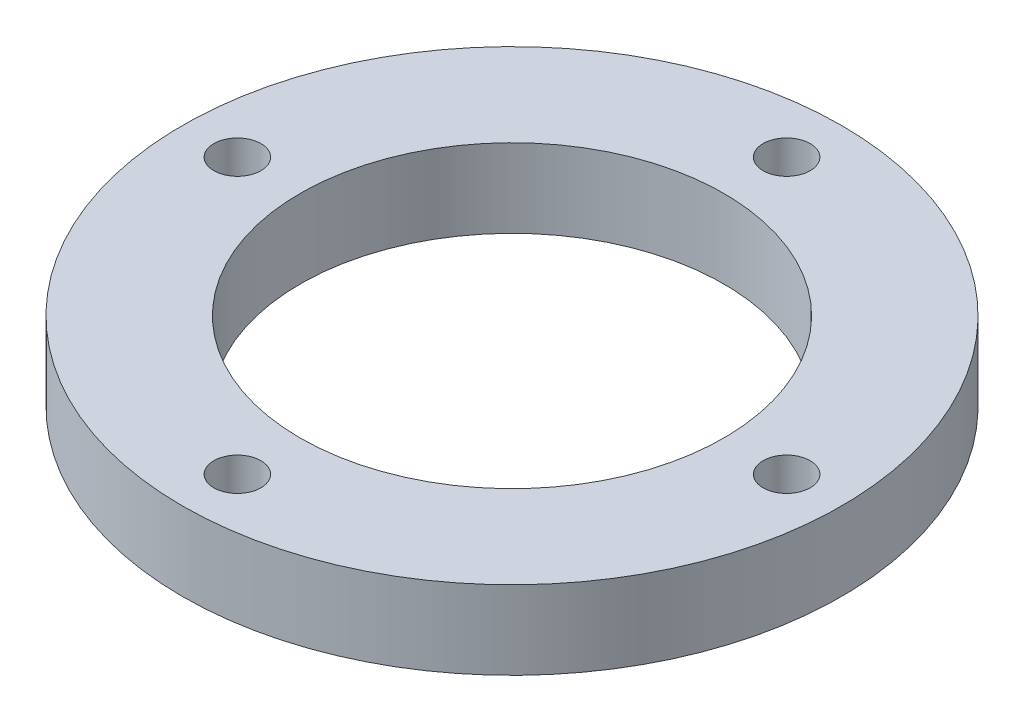
SolidWorks part; units mm, degrees
ref_plane "前视基准面" through (0, 0, 0) normal (0, 0, 1) x (1, 0, 0)
ref_plane "上视基准面" through (0, 0, 0) normal (0, 1, 0) x (1, 0, 0)
ref_plane "右视基准面" through (0, 0, 0) normal (1, 0, 0) x (0, 0, -1)
sketch "草图1" plane through (0, 0, 0) normal (0, 1, 0) x (1, 0, 0)
  circle A0 centre (0, 0) radius 21
  circle A1 centre (0, 0) radius 17.5 construction
  circle A2 centre (0, 0) radius 13.5
  circle A3 centre (0, 17.5) radius 1.5
  circle A4 centre (17.5, 0) radius 1.5
  circle A5 centre (0, -17.5) radius 1.5
  circle A6 centre (-17.5, 0) radius 1.5
  point P7 (-26.634, -1.6887)
  point P8 (0, 0)
  point P16 (0, 0)
  dimension "D1" = 42
  dimension "D2" = 35
  dimension "D3" = 3
  dimension "D4" = 27
  dimension "D5" = 4
extrude "凸台-拉伸1" add sketch "草图1" along normal mid plane 5
